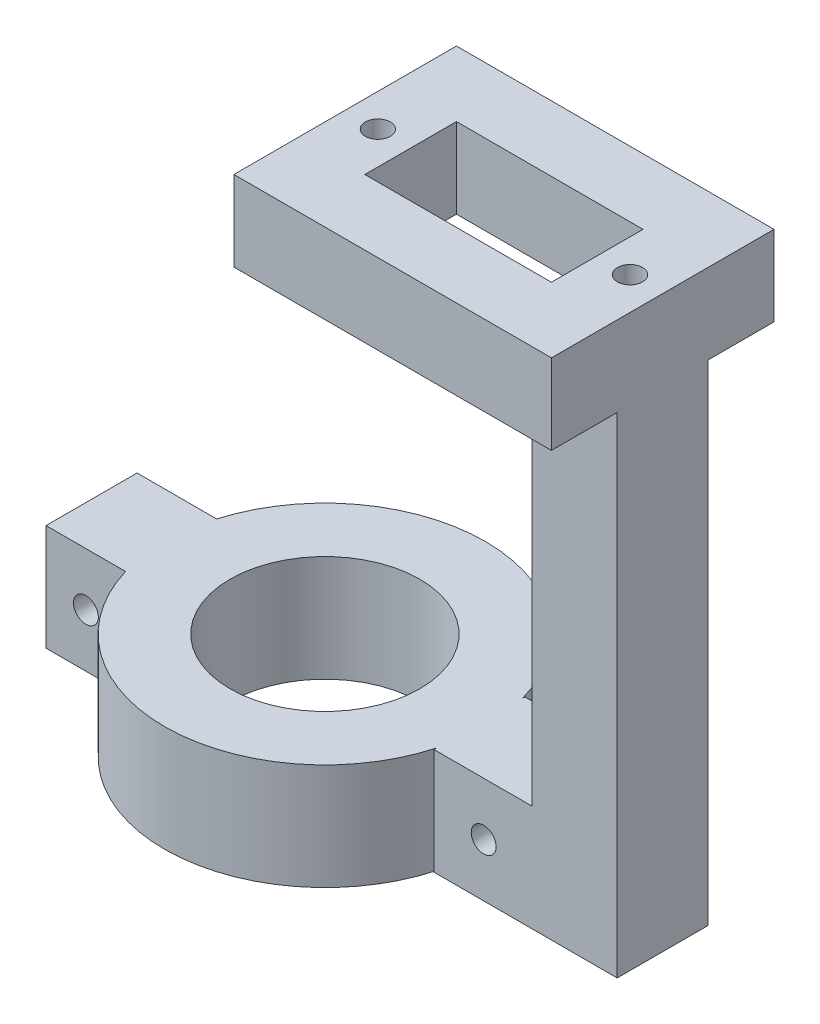
SolidWorks part; units mm, degrees
ref_plane "前基準面" through (0, 0, 0) normal (0, 0, 1) x (1, 0, 0)
ref_plane "上基準面" through (0, 0, 0) normal (0, 1, 0) x (1, 0, 0)
ref_plane "右基準面" through (0, 0, 0) normal (1, 0, 0) x (0, 0, -1)
sketch "草圖1" plane through (0, 0, 0) normal (0, 1, 0) x (1, 0, 0)
  line L1 (-14.255, 7) -> (14.255, 7)
  line L2 (-14.255, 7) -> (-14.255, -7)
  line L3 (-14.255, -7) -> (14.255, -7)
  line L4 (14.255, 7) -> (14.255, -7)
  line L5 (-14.255, 7) -> (14.255, -7) construction
  line L6 (-14.255, -7) -> (14.255, 7) construction
  point P0 (0, 0)
  dimension "D1" = 14
  dimension "D2" = 28.51
extrude "伸長-薄件1" add sketch "草圖1" along normal blind 12.25 thin thin type one direction wall 10
sketch "草圖2" plane through (0, 12.25, 0) normal (0, 1, 0) x (1, 0, 0)
  line L0 (-1014.255, 0) -> (48985.745, 0) construction
  line L1 (-14.255, 7) -> (-14.255, -7) construction
  line L2 (-19.255, -988.4004) -> (-19.255, 49011.5996) construction
  line L3 (-24.255, 17) -> (-19.255, 17) construction
  line L4 (-24.255, 17) -> (-24.255, 11.5996) construction
  line L5 (-24.255, 11.5996) -> (-19.255, 11.5996) construction
  line L6 (-19.255, 17) -> (-19.255, 11.5996) construction
  line L7 (24.255, 17) -> (19.255, 17) construction
  line L8 (24.255, 17) -> (24.255, 12.4477) construction
  line L9 (24.255, 12.4477) -> (19.255, 12.4477) construction
  line L10 (19.255, 17) -> (19.255, 12.4477) construction
  line L11 (19.255, -987.5523) -> (19.255, 49012.4477) construction
  circle A0 centre (-19.255, 0) radius 1.91
  circle A1 centre (19.255, 0) radius 1.91
  point P5 (-14.255, 0)
  dimension "D3" = 3.82
  dimension "D4" = 3.82
  dimension "D1" = 5
  dimension "D2" = 5
extrude "除料-伸長1" cut sketch "草圖2" against normal through all
sketch "草圖4" plane through (0, 0, 0) normal (0, -1, 0) x (1, 0, 0)
  line L0 (-1000, 0) -> (49000, 0) construction
  line L1 (24.255, 17) -> (24.255, -17) construction
  line L2 (11.255, 6.955) -> (24.255, 6.955)
  line L3 (11.255, 6.955) -> (11.255, -6.955)
  line L4 (11.255, -6.955) -> (24.255, -6.955)
  line L5 (24.255, 6.955) -> (24.255, -6.955)
  line L6 (11.255, 6.955) -> (24.255, -6.955) construction
  line L7 (11.255, -6.955) -> (24.255, 6.955) construction
  point P1 (17.755, 0)
  dimension "D1" = 13.91
  dimension "D2" = 13
extrude "填料-伸長1" add sketch "草圖4" along normal blind 74.82
sketch "草圖5" plane through (11.255, 0, 0) normal (-1, 0, 0) x (0, 0, 1)
  line L0 (6.955, -74.82) -> (6.955, 0) construction
  line L1 (-6.955, -74.82) -> (6.955, -74.82)
  line L2 (-6.955, -74.82) -> (-6.955, -58.59)
  line L3 (-6.955, -58.59) -> (6.955, -58.59)
  line L4 (6.955, -74.82) -> (6.955, -58.59)
  dimension "D1" = 16.23
extrude "填料-伸長2" add sketch "草圖5" along normal blind 15
sketch "草圖7" plane through (3.6267, -74.82, 0) normal (0, -1, 0) x (1, 0, 0)
  circle A0 centre (-30.9782, 0) radius 14.5
  dimension "D1" = 29
extrude "伸長-薄件2" add sketch "草圖7" against normal blind 16.23 thin
ref_plane "平面1" through (-60, 0, 0) normal (1, 0, 0) x (0, 0, -1)
sketch "草圖12" plane through (0, 0, -6.955) normal (0, 0, -1) x (-1, 0, 0)
  line L0 (-996.255, -66.705) -> (49003.745, -66.705) construction
  line L1 (3.745, -74.82) -> (3.745, -58.59) construction
  line L2 (-3.755, -1058.59) -> (-3.755, 48941.41) construction
  line L3 (3.745, -58.59) -> (-11.255, -58.59) construction
  circle A0 centre (-3.8567, -66.705) radius 1.9
  point P5 (3.745, -66.705)
  point P10 (-3.755, -58.59)
  dimension "D1" = 3.8
extrude "除料-伸長4" cut sketch "草圖12" against normal through all
ref_plane "平面2" through (-55, 0, 0) normal (1, 0, 0) x (0, 0, -1)
sketch "草圖13" plane through (-55, 0, 0) normal (1, 0, 0) x (0, 0, -1)
  line L1 (6.955, -58.59) -> (-6.955, -58.59)
  line L2 (6.955, -58.59) -> (6.955, -74.82)
  line L3 (6.955, -74.82) -> (-6.955, -74.82)
  line L4 (-6.955, -58.59) -> (-6.955, -74.82)
extrude "填料-伸長3" add sketch "草圖13" along normal blind 10 and the other way blind 8
sketch "草圖14" plane through (0, 0, -6.955) normal (0, 0, -1) x (-1, 0, 0)
  line L0 (-949.1564, -66.705) -> (49050.8436, -66.705) construction
  line L1 (50.8436, -58.59) -> (50.8436, -74.82) construction
  line L2 (56.9218, -1058.59) -> (56.9218, 48941.41) construction
  line L3 (63, -58.59) -> (50.8436, -58.59) construction
  circle A0 centre (56.908, -66.705) radius 1.9
  point P5 (50.8436, -66.705)
  point P10 (56.9218, -58.59)
  dimension "D1" = 3.8
extrude "除料-伸長5" cut sketch "草圖14" against normal through all
